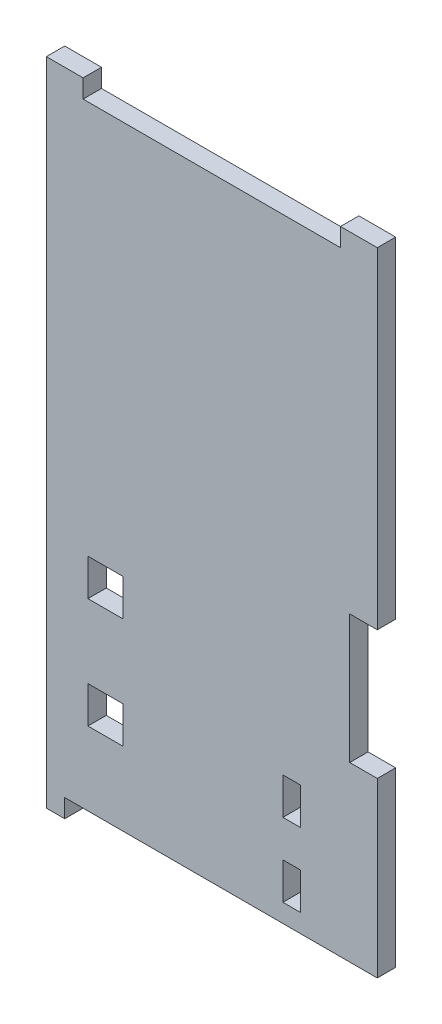
SolidWorks part; units mm, degrees
ref_plane "Plan de face" through (0, 0, 0) normal (0, 0, 1) x (1, 0, 0)
ref_plane "Plan de dessus" through (0, 0, 0) normal (0, 1, 0) x (1, 0, 0)
ref_plane "Plan de droite" through (0, 0, 0) normal (1, 0, 0) x (0, 0, -1)
sketch "Esquisse1" plane through (0, 0, 0) normal (0, 0, 1) x (1, 0, 0)
  line L0 (90, 82) -> (90, 167)
  line L1 (5, 0) -> (90, 0)
  line L2 (0, 0) -> (0, 167)
  line L3 (10, 167) -> (80, 167)
  line L4 (90, 0) -> (90, 47)
  line L5 (90, 82) -> (82.5, 82)
  line L6 (0, 167) -> (0, 172)
  line L7 (0, 172) -> (10, 172)
  line L8 (10, 167) -> (10, 172)
  line L9 (0, 0) -> (0, -5)
  line L10 (90, 167) -> (90, 172)
  line L11 (90, 172) -> (80, 172)
  line L12 (80, 167) -> (80, 172)
  line L13 (0, -5) -> (5, -5)
  line L14 (5, 0) -> (5, -5)
  line L15 (64.3348, 35) -> (64.3348, 25)
  line L16 (90, 47) -> (82.5, 47)
  line L17 (82.5, 82) -> (82.5, 47)
  line L18 (64.3348, 35) -> (69.1423, 35)
  line L19 (64.3348, 25) -> (69.1423, 25)
  line L20 (69.1423, 35) -> (69.1423, 25)
  line L21 (71.3405, 35) -> (66.533, 35) construction
  line L22 (64.3348, 35) -> (64.3348, 25) construction
  line L23 (69.1423, 35) -> (69.1423, 25) construction
  line L24 (18.5374, 30) -> (3.1837, 30) construction
  line L25 (64.3348, 15) -> (69.1423, 15)
  line L26 (64.3348, 15) -> (64.3348, 5)
  line L27 (64.3348, 5) -> (69.1423, 5)
  line L28 (69.1423, 15) -> (69.1423, 5)
  line L29 (11.3034, 30) -> (20.8832, 30)
  line L30 (11.3034, 30) -> (11.3034, 20)
  line L31 (11.3034, 20) -> (20.8832, 20)
  line L32 (20.8832, 30) -> (20.8832, 20)
  line L33 (3.1837, 20) -> (18.5374, 20) construction
  line L36 (21.1471, 30) -> (5.7933, 30) construction
  line L37 (11.3034, 60) -> (20.8832, 60)
  line L38 (11.3034, 60) -> (11.3034, 50)
  line L39 (11.3034, 50) -> (20.8832, 50)
  line L40 (20.8832, 60) -> (20.8832, 50)
  dimension "D1" = 167
  dimension "D2" = 90
  dimension "D3" = 10
  dimension "D4" = 5
  dimension "D5" = 5
  dimension "D6" = 7.5
  dimension "D7" = 35
  dimension "D8" = 82
  dimension "D9" = 10
  dimension "D10" = 10
  dimension "D11" = 10
extrude "Boss.-Extru.1" add sketch "Esquisse1" along normal blind 5
